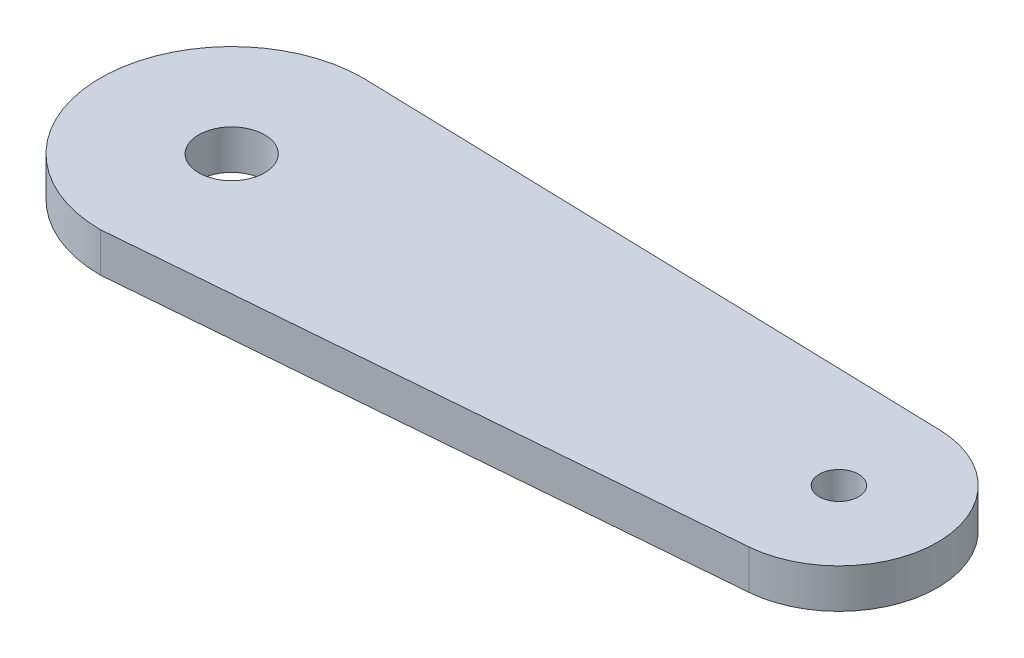
SolidWorks part; units mm, degrees
ref_plane "Front Plane" through (0, 0, 0) normal (0, 0, 1) x (1, 0, 0)
ref_plane "Top Plane" through (0, 0, 0) normal (0, 1, 0) x (1, 0, 0)
ref_plane "Right Plane" through (0, 0, 0) normal (1, 0, 0) x (0, 0, -1)
sketch "Sketch1" plane through (0, 0, 0) normal (0, 1, 0) x (1, 0, 0)
  line L0 (0, 10) -> (45.1912, 8.7436)
  line L1 (0, -10) -> (45.601, -6.2279)
  circle A0 centre (0, 0) radius 10
  circle A1 centre (44.9827, 1.2465) radius 7.5
  dimension "D2" = 20
  dimension "D3" = 15
  dimension "D1" = 45
extrude "Boss-Extrude1" add sketch "Sketch1" along normal blind 3 contours L1 A0 L0 | A1 L0 A0 L1 | A1 L1
sketch "Sketch2" plane through (0, 3, 0) normal (0, 1, 0) x (1, 0, 0)
  circle A0 centre (0, 0) radius 2.51
  circle A1 centre (44.9827, 1.2465) radius 1.495
  dimension "D1" = 5.02
  dimension "D2" = 2.99
extrude "Cut-Extrude1" cut sketch "Sketch2" against normal up to next
